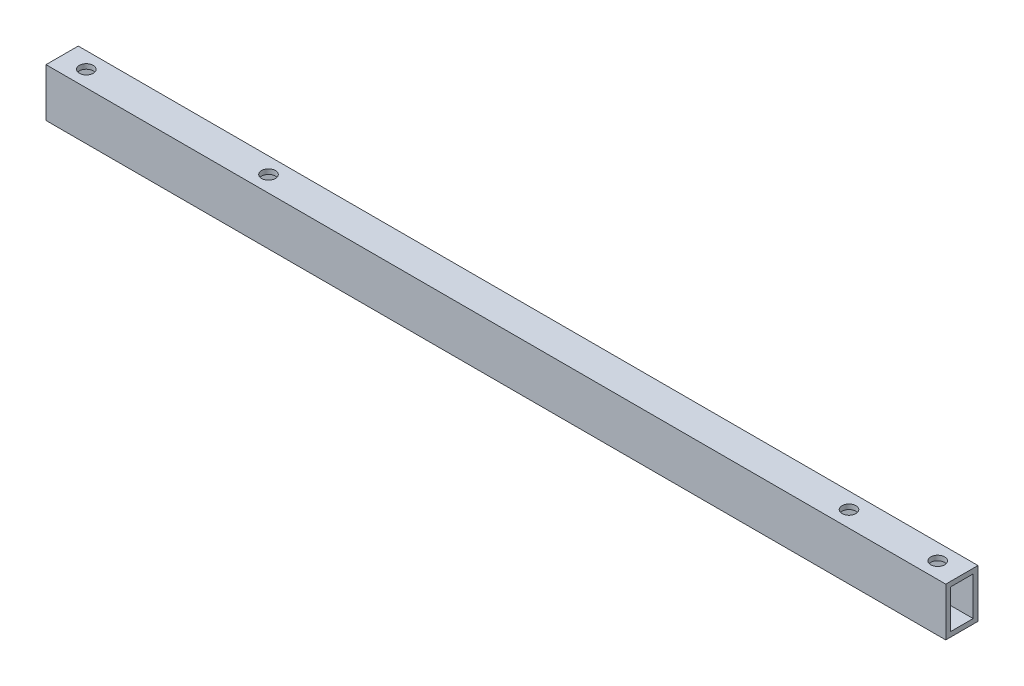
SolidWorks part; units mm, degrees
material "5052-H34"
ref_plane "正面" through (0, 0, 0) normal (0, 0, 1) x (1, 0, 0)
ref_plane "平面" through (0, 0, 0) normal (0, 1, 0) x (1, 0, 0)
ref_plane "右側面" through (0, 0, 0) normal (1, 0, 0) x (0, 0, -1)
sketch "ｽｹｯﾁ1" plane through (0, 0, 0) normal (1, 0, 0) x (0, 0, -1)
  line L1 (-5, 7.5) -> (5, 7.5)
  line L2 (-5, 7.5) -> (-5, -7.5)
  line L3 (-5, -7.5) -> (5, -7.5)
  line L4 (5, 7.5) -> (5, -7.5)
  line L5 (-5, 7.5) -> (5, -7.5) construction
  line L6 (-5, -7.5) -> (5, 7.5) construction
  point P0 (0, 0)
  dimension "D1" = 10
  dimension "D2" = 15
extrude "押し出し-薄板1" add sketch "ｽｹｯﾁ1" along normal blind 279 thin
sketch "ｽｹｯﾁ2" plane through (0, 7.5, 0) normal (0, 1, 0) x (1, 0, 0)
  line L0 (139.5, 5) -> (139.5, -5) construction
  line L1 (279, 5) -> (0, 5) construction
  line L2 (279, -5) -> (0, -5) construction
  line L3 (139.5, 0) -> (271.5, 0) construction
  line L4 (279, 5) -> (279, -5) construction
  line L5 (0, 5) -> (0, -5) construction
  circle A0 centre (271.5, 0) radius 2.15
  circle A2 centre (7.5, 0) radius 2.15
  circle A3 centre (64, 0) radius 2.15
  circle A4 centre (244, 0) radius 2.15
  dimension "D1" = 7.5
  dimension "D2" = 4.3
  dimension "D4" = 35
  dimension "D5" = 7.5
  dimension "D6" = 5
  dimension "D7" = 4.3
  dimension "D3" = 180
extrude "ｶｯﾄ - 押し出し1" cut sketch "ｽｹｯﾁ2" against normal through all
